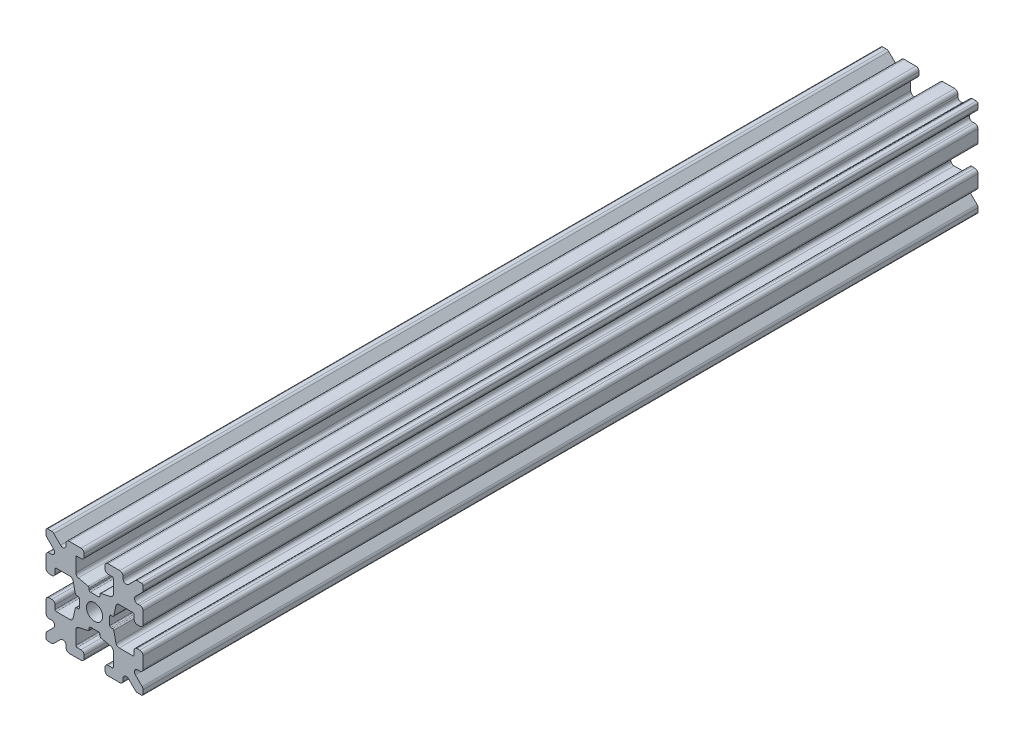
SolidWorks part; units mm, degrees
ref_plane "Front Plane" through (0, 0, 0) normal (0, 0, 1) x (1, 0, 0)
ref_plane "Top Plane" through (0, 0, 0) normal (0, 1, 0) x (1, 0, 0)
ref_plane "Right Plane" through (0, 0, 0) normal (1, 0, 0) x (0, 0, -1)
sketch "Sketch1" plane through (0, 0, 0) normal (0, 0, 1) x (1, 0, 0)
  line L1 (-7.5, -7.5) -> (7.5, -7.5)
  line L2 (-7.5, -7.5) -> (-7.5, 7.5)
  line L3 (-7.5, 7.5) -> (7.5, 7.5)
  line L4 (7.5, -7.5) -> (7.5, 7.5)
  line L5 (-7.5, -7.5) -> (7.5, 7.5) construction
  line L6 (-7.5, 7.5) -> (7.5, -7.5) construction
  circle A0 centre (0, 0) radius 1.25
  point P0 (0, 0)
  dimension "D2" = 2.5
  dimension "D1" = 15
extrude "Boss-Extrude1" add sketch "Sketch1" along normal mid plane 129
fillet "Fillet1" radius 0.25 4 edges at (7.5, -7.5, 0) (-7.5, -7.5, 0) (7.5, 7.5, 0) (-7.5, 7.5, 0)
sketch "Sketch2" plane through (0, 0, 64.5) normal (0, 0, 1) x (1, 0, 0)
  line L0 (-7.5, 7.25) -> (-7.5, -7.25) construction
  line L1 (-7.5, 1.6) -> (-6.1, 1.6)
  line L2 (-7.5, 1.6) -> (-7.5, -1.6)
  line L3 (-7.5, -1.6) -> (-6.1, -1.6)
  line L4 (-6.1, 1.6) -> (-6.1, 2.9)
  line L5 (0, 0) -> (-12.1036, 0) construction
  line L6 (-6.1, -2.9) -> (-3.4, -2.9)
  line L7 (0, 0) -> (-7.25, 7.25) construction
  line L8 (-6.1, 2.9) -> (-3.4, 2.9)
  line L9 (-3.4, -2.9) -> (-3.4, 2.9)
  line L10 (55, 0) -> (-55, 0) construction
  line L11 (-6.1, -2.9) -> (-6.1, -1.6)
  line L12 (2.9, 6.1) -> (1.6, 6.1)
  line L13 (2.9, 3.4) -> (-2.9, 3.4)
  line L14 (-2.9, 6.1) -> (-2.9, 3.4)
  line L15 (2.9, 6.1) -> (2.9, 3.4)
  line L16 (-1.6, 6.1) -> (-2.9, 6.1)
  line L17 (1.6, 7.5) -> (1.6, 6.1)
  line L18 (-1.6, 7.5) -> (1.6, 7.5)
  line L19 (-1.6, 7.5) -> (-1.6, 6.1)
  line L20 (-1.6, -7.5) -> (-1.6, -6.1)
  line L21 (-1.6, -7.5) -> (1.6, -7.5)
  line L22 (1.6, -7.5) -> (1.6, -6.1)
  line L23 (-1.6, -6.1) -> (-2.9, -6.1)
  line L24 (2.9, -6.1) -> (2.9, -3.4)
  line L25 (-2.9, -6.1) -> (-2.9, -3.4)
  line L26 (2.9, -3.4) -> (-2.9, -3.4)
  line L27 (2.9, -6.1) -> (1.6, -6.1)
  line L28 (6.1, -2.9) -> (6.1, -1.6)
  line L29 (3.4, -2.9) -> (3.4, 2.9)
  line L30 (6.1, 2.9) -> (3.4, 2.9)
  line L31 (6.1, -2.9) -> (3.4, -2.9)
  line L32 (6.1, 1.6) -> (6.1, 2.9)
  line L33 (7.5, -1.6) -> (6.1, -1.6)
  line L34 (7.5, 1.6) -> (7.5, -1.6)
  line L35 (7.5, 1.6) -> (6.1, 1.6)
  dimension "D1" = 3.2
  dimension "D2" = 5.8
  dimension "D3" = 1.4
  dimension "D4" = 2.7
extrude "Cut-Extrude1" cut sketch "Sketch2" against normal through all
sketch "Sketch4" plane through (0, 0, 64.5) normal (0, 0, 1) x (1, 0, 0)
  line L0 (-3.4, 2.9) -> (-2.75, 0)
  line L1 (55, 0) -> (-55, 0) construction
  line L2 (-2.75, 0) -> (-3.4, -2.9)
  line L3 (-3.4, -2.9) -> (-3.4, 2.9) construction
  line L4 (-3.4, 2.9) -> (-3.4, -2.9)
  line L5 (-2.9, 3.4) -> (0, 2.75)
  line L6 (0, 2.75) -> (2.9, 3.4)
  line L7 (2.9, 3.4) -> (-2.9, 3.4)
  line L8 (3.4, 2.9) -> (2.75, 0)
  line L9 (2.75, 0) -> (3.4, -2.9)
  line L10 (3.4, -2.9) -> (3.4, 2.9)
  line L11 (-2.9, -3.4) -> (0, -2.75)
  line L12 (0, -2.75) -> (2.9, -3.4)
  line L13 (2.9, -3.4) -> (-2.9, -3.4)
  circle A2 centre (0, 0) radius 2.75
  circle A3 centre (0, 0) radius 2.75 construction
  dimension "D1" = 1.5
extrude "Cut-Extrude3" cut sketch "Sketch4" against normal through all
fillet "Fillet3" radius 0.5 16 edges at (-6.1, -1.6, 0) (-7.5, -1.6, 0) (-6.1, 1.6, 0) (-7.5, 1.6, 0) (-1.6, -7.5, 0) (-1.6, -6.1, 0) (1.6, -7.5, 0) (1.6, -6.1, 0) (6.1, -1.6, 0) (7.5, -1.6, 0) (7.5, 1.6, 0) (6.1, 1.6, 0) (1.6, 7.5, 0) (1.6, 6.1, 0) (-1.6, 7.5, 0) (-1.6, 6.1, 0)
fillet "Fillet4" radius 0.5 8 edges at (-3.4, 2.9, 0) (-3.4, -2.9, 0) (2.9, -3.4, 0) (-2.9, -3.4, 0) (3.4, -2.9, 0) (3.4, 2.9, 0) (-2.9, 3.4, 0) (2.9, 3.4, 0)
fillet "Fillet5" radius 3 4 edges at (0, -2.75, 0) (2.75, 0, 0) (-2.75, 0, 0) (0, 2.75, 0)
fillet "Fillet6" radius 0.2 8 edges at (-2.9, -6.1, 0) (2.9, -6.1, 0) (6.1, -2.9, 0) (6.1, 2.9, 0) (2.9, 6.1, 0) (-2.9, 6.1, 0) (-6.1, -2.9, 0) (-6.1, 2.9, 0)
sketch "Sketch5" plane through (0, 0, 64.5) normal (0, 0, 1) x (1, 0, 0)
  line L0 (0, 0) -> (-7.25, 7.25) construction
  line L1 (-7.5, 6.4393) -> (-5.4607, 4.4)
  line L2 (-6.4393, 7.5) -> (-4.4, 5.4607)
  line L3 (-7.5, 4.4) -> (-5.4607, 4.4)
  line L4 (-3.8003, 2.9) -> (-5.9, 2.9) construction
  line L5 (0, 0) -> (-12.1819, 0) construction
  line L6 (-4.4, 7.5) -> (-4.4, 5.4607)
  line L7 (-2.9, 5.9) -> (-2.9, 3.8003) construction
  line L8 (-7.5, 6.4393) -> (-7.5, 4.4)
  line L9 (-7.5, 7.25) -> (-7.5, 2.1) construction
  line L10 (2.1, -7.5) -> (7.25, -7.5) construction
  line L11 (7.5, -7.25) -> (7.5, -2.1) construction
  line L12 (7.25, 7.5) -> (2.1, 7.5) construction
  line L13 (-2.1, 7.5) -> (-7.25, 7.5) construction
  line L14 (-4.4, 7.5) -> (-6.4393, 7.5)
  line L16 (55, 0) -> (-55, 0) construction
  line L17 (0, 0) -> (0, 10.993) construction
  line L18 (0, -54.6431) -> (0, 54.6431) construction
  line L20 (4.4, 7.5) -> (6.4393, 7.5)
  line L22 (7.5, 6.4393) -> (7.5, 4.4)
  line L23 (4.4, 7.5) -> (4.4, 5.4607)
  line L24 (7.5, 4.4) -> (5.4607, 4.4)
  line L25 (6.4393, 7.5) -> (4.4, 5.4607)
  line L26 (7.5, 6.4393) -> (5.4607, 4.4)
  line L27 (7.5, -6.4393) -> (5.4607, -4.4)
  line L28 (6.4393, -7.5) -> (4.4, -5.4607)
  line L29 (7.5, -4.4) -> (5.4607, -4.4)
  line L30 (4.4, -7.5) -> (4.4, -5.4607)
  line L31 (7.5, -6.4393) -> (7.5, -4.4)
  line L33 (4.4, -7.5) -> (6.4393, -7.5)
  line L36 (-4.4, -7.5) -> (-6.4393, -7.5)
  line L38 (-7.5, -6.4393) -> (-7.5, -4.4)
  line L39 (-4.4, -7.5) -> (-4.4, -5.4607)
  line L40 (-7.5, -4.4) -> (-5.4607, -4.4)
  line L41 (-6.4393, -7.5) -> (-4.4, -5.4607)
  line L42 (-7.5, -6.4393) -> (-5.4607, -4.4)
  dimension "D1" = 1.5
  dimension "D2" = 1.5
  dimension "D3" = 1.5
extrude "Cut-Extrude4" cut sketch "Sketch5" against normal through all
fillet "Fillet8" radius 0.5 24 edges at (-5.4607, 4.4, 0) (-7.5, 4.4, 0) (-5.4607, -4.4, 0) (-7.5, -4.4, 0) (-4.4, -7.5, 0) (-4.4, -5.4607, 0) (4.4, -7.5, 0) (4.4, -5.4607, 0) (5.4607, -4.4, 0) (7.5, -4.4, 0) (7.5, 4.4, 0) (5.4607, 4.4, 0) (4.4, 5.4607, 0) (4.4, 7.5, 0) (-4.4, 5.4607, 0) (-4.4, 7.5, 0) (-6.4393, 7.5, 0) (-7.5, 6.4393, 0) (6.4393, 7.5, 0) (7.5, 6.4393, 0) (6.4393, -7.5, 0) (7.5, -6.4393, 0) (-6.4393, -7.5, 0) (-7.5, -6.4393, 0)
sketch "Sketch6" plane through (0, 0, 64.5) normal (0, 0, 1) x (1, 0, 0)
  line L0 (0, 0) -> (0, 11.013) construction
  line L1 (0.6561, 2.8971) -> (2.1235, 2.8971) construction
  line L2 (0, -54.6431) -> (0, 54.6431) construction
  line L3 (0, 0) -> (7.25, 7.25) construction
  line L4 (7.5, 0.8255) -> (7.5, -0.8255)
  line L5 (2.3471, 0.8255) -> (7.5, 0.8255)
  line L6 (0, 0) -> (12.4016, 0) construction
  line L7 (0.8255, -7.5) -> (-0.8255, -7.5)
  line L8 (2.3471, -0.8255) -> (2.3471, 0.8255)
  line L9 (0.8255, -2.3471) -> (0.8255, -7.5)
  line L10 (7.5, -0.8255) -> (2.3471, -0.8255)
  line L11 (-7.5, -0.8255) -> (-2.3471, -0.8255)
  line L12 (-2.3471, -0.8255) -> (-2.3471, 0.8255)
  line L13 (-0.8255, -2.3471) -> (0.8255, -2.3471)
  line L14 (-0.8255, 7.5) -> (-0.8255, 2.3471)
  line L15 (-0.8255, 2.3471) -> (0.8255, 2.3471)
  line L16 (-0.8255, -7.5) -> (-0.8255, -2.3471)
  line L17 (0.8255, 2.3471) -> (0.8255, 7.5)
  line L18 (0.8255, 7.5) -> (-0.8255, 7.5)
  line L19 (3.9, 7.5) -> (2.1, 7.5) construction
  line L20 (-2.3471, 0.8255) -> (-7.5, 0.8255)
  line L21 (-7.5, 0.8255) -> (-7.5, -0.8255)
  point P5 (0, -2.5973)
  point P7 (0, 2.5973)
  dimension "D3" = 0.55
  dimension "D1" = 1.651
extrude "Cut-Extrude5" cut sketch "Sketch6" against normal through all
fillet "Fillet10" radius 0.2 16 edges at (-2.935, 0.8255, 0) (-2.935, -0.8255, 0) (2.935, -0.8255, 0) (2.935, 0.8255, 0) (0.8255, 2.935, 0) (-0.8255, 2.935, 0) (-2.3471, 0.8255, 0) (-2.3471, -0.8255, 0) (0.8255, 2.3471, 0) (-0.8255, 2.3471, 0) (2.3471, 0.8255, 0) (2.3471, -0.8255, 0) (0.8255, -2.935, 0) (0.8255, -2.3471, 0) (-0.8255, -2.3471, 0) (-0.8255, -2.935, 0)
